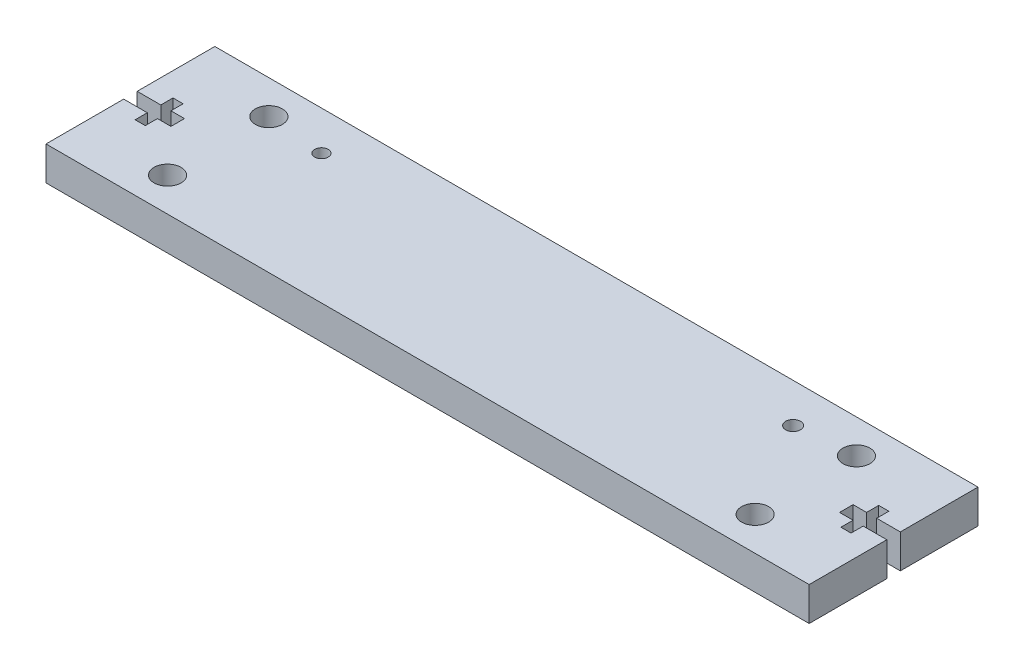
SolidWorks part; units mm, degrees
material "Acrílico (médio-alto impacto)"
ref_plane "Plano frontal" through (0, 0, 0) normal (0, 0, 1) x (1, 0, 0)
ref_plane "Plano superior" through (0, 0, 0) normal (0, 1, 0) x (1, 0, 0)
ref_plane "Plano direito" through (0, 0, 0) normal (1, 0, 0) x (0, 0, -1)
sketch "Esboço1" plane through (0, 0, 0) normal (0, 1, 0) x (1, 0, 0)
  line L1 (-47.2683, 18.484) -> (65.7317, 18.484)
  line L2 (-47.2683, 18.484) -> (-47.2683, -6.516)
  line L3 (-47.2683, -6.516) -> (65.7317, -6.516)
  line L4 (65.7317, 18.484) -> (65.7317, -6.516)
  dimension "D1" = 25
extrude "Ressalto-extrusão1" add sketch "Esboço1" along normal blind 5
sketch "Esboço2" plane through (0, 5, 0) normal (0, 1, 0) x (1, 0, 0)
  line L0 (65.7317, -6.516) -> (65.7317, 18.484) construction
  line L1 (65.7317, 4.984) -> (62.2317, 4.984)
  line L2 (65.7317, 4.984) -> (65.7317, 6.984)
  line L3 (65.7317, 6.984) -> (62.2317, 6.984)
  line L4 (60.7317, 8.784) -> (60.7317, 6.984)
  line L5 (60.7317, 4.984) -> (60.7317, 3.184)
  line L6 (62.2317, 6.984) -> (62.2317, 8.784)
  line L7 (60.7317, 3.184) -> (62.2317, 3.184)
  line L8 (60.7317, 6.984) -> (58.7317, 6.984)
  line L9 (60.7317, 8.784) -> (62.2317, 8.784)
  line L10 (62.2317, 3.184) -> (62.2317, 4.984)
  line L12 (60.7317, 4.984) -> (58.7317, 4.984)
  line L13 (58.7317, 6.984) -> (58.7317, 4.984)
  line L18 (-47.2683, -6.516) -> (65.7317, -6.516) construction
  dimension "D2" = 1.8
  dimension "D3" = 1.8
  dimension "D4" = 3.5
  dimension "D7" = 11.5
  dimension "D8" = 2
extrude "Corte-extrusão1" cut sketch "Esboço2" against normal blind 5
ref_plane "Plano1" through (9.2317, 0, 0) normal (1, 0, 0) x (0, 0, -1)
mirror "Espelhar1" about plane through (9.2317, 0, 0) normal (1, 0, 0) of "Corte-extrusão1"
sketch "Esboço4" plane through (0, 5, 0) normal (0, 1, 0) x (1, 0, 0)
  line L0 (-47.2683, 18.484) -> (-47.2683, 6.984) construction
  line L1 (65.7317, 18.484) -> (-47.2683, 18.484) construction
  line L2 (65.7317, 6.984) -> (65.7317, 18.484) construction
  circle A0 centre (-25.6883, 12.684) radius 1
  circle A1 centre (44.1517, 12.684) radius 1.1
  dimension "D1" = 21.58
  dimension "D2" = 5.8
  dimension "D3" = 21.58
extrude "Corte-extrusão2" cut sketch "Esboço4" against normal blind 76
sketch "Esboço5" plane through (0, 5, 0) normal (0, 1, 0) x (1, 0, 0)
  line L0 (-47.2683, -6.516) -> (65.7317, -6.516) construction
  line L1 (65.7317, 6.984) -> (65.7317, 18.484) construction
  line L2 (65.7317, 18.484) -> (-47.2683, 18.484) construction
  line L3 (-47.2683, 18.484) -> (-47.2683, 6.984) construction
  circle A0 centre (-34.2683, 13.484) radius 2
  circle A1 centre (-34.2683, -1.516) radius 2
  circle A2 centre (52.7317, 13.484) radius 2
  circle A3 centre (52.7317, -1.516) radius 2
  dimension "D1" = 5
  dimension "D2" = 13
  dimension "D3" = 13
  dimension "D4" = 5
  dimension "D5" = 5
  dimension "D6" = 13
  dimension "D7" = 13
  dimension "D8" = 5
extrude "Corte-extrusão3" cut sketch "Esboço5" against normal blind 10
